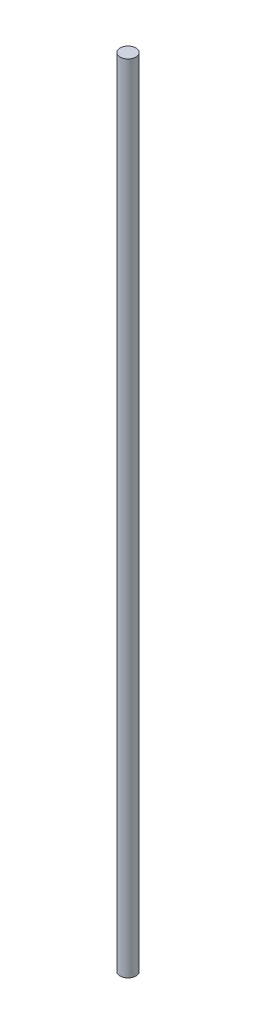
SolidWorks part; units mm, degrees
material "1023 Carbon Steel Sheet (SS)"
ref_plane "Front Plane" through (0, 0, 0) normal (0, 0, 1) x (1, 0, 0)
ref_plane "Top Plane" through (0, 0, 0) normal (0, 1, 0) x (1, 0, 0)
ref_plane "Right Plane" through (0, 0, 0) normal (1, 0, 0) x (0, 0, -1)
sketch "Sketch1" plane through (0, 0, 0) normal (0, 1, 0) x (1, 0, 0)
  circle A0 centre (0, 0) radius 1.5
  dimension "D1" = 3
extrude "Boss-Extrude1" add sketch "Sketch1" along normal blind 150
thread "Thread1" pitch 0.5 start angle 0, offset 0.0001, length 0, pitch 0.5, diameter 3
ref_plane "Plane1" through (-1.5, 299.9999, 0) normal (0, 0, 1) x (-1, 0, 0)
sketch "Thread Profile1" plane through (-1.5, 299.9999, 0) normal (0, 0, 1) x (-1, 0, 0)
  line L0 (0, 0) -> (0, 0.5) construction
  line L11 (0, 0) -> (0, 0.4375)
  line L12 (0, 0.4375) -> (-0.2706, 0.2812)
  line L13 (-0.2706, 0.2812) -> (-0.2706, 0.1562)
  line L15 (-0.2706, 0.1562) -> (0, 0)
  line L17 (-0.2706, 0.2187) -> (0, 0.2187) construction
  point P2 (0, 0)
  dimension "Pitch" = 0.5
  dimension "Profile_Angle" = 60
  dimension "Profile_Land" = 0.125
  dimension "Profile_Height" = 0.2706
